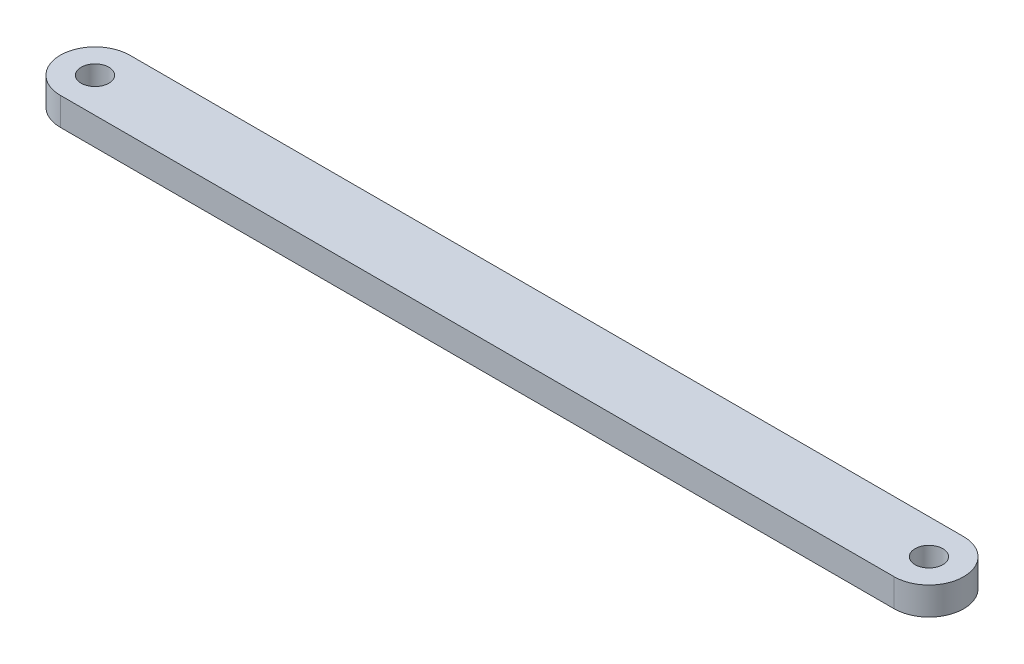
SolidWorks part; units mm, degrees
ref_plane "Front Plane" through (0, 0, 0) normal (0, 0, 1) x (1, 0, 0)
ref_plane "Top Plane" through (0, 0, 0) normal (0, 1, 0) x (1, 0, 0)
ref_plane "Right Plane" through (0, 0, 0) normal (1, 0, 0) x (0, 0, -1)
sketch "Sketch1" plane through (0, 0, 0) normal (0, 1, 0) x (1, 0, 0)
  line L0 (0, 0) -> (60, 0) construction
  line L1 (0, 2.5) -> (60, 2.5)
  line L2 (0, -2.5) -> (60, -2.5)
  arc A0 (0, 2.5) -> (0, -2.5) centre (0, 0) ccw
  arc A1 (60, -2.5) -> (60, 2.5) centre (60, 0) ccw
  circle A2 centre (0, 0) radius 1
  circle A3 centre (60, 0) radius 1
  point P3 (30, 0)
  dimension "D2" = 2.5
  dimension "D4" = 2
  dimension "D5" = 2
  dimension "D1" = 60
extrude "Boss-Extrude1" add sketch "Sketch1" along normal blind 2
